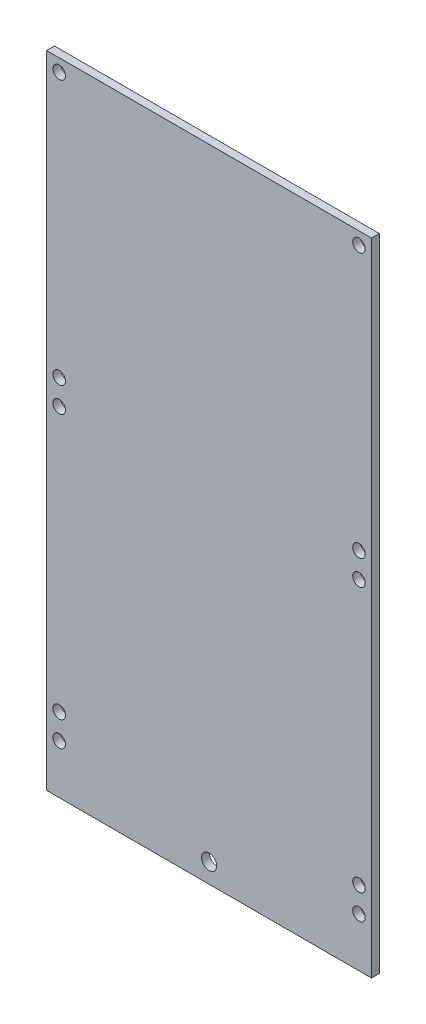
SolidWorks part; units mm, degrees
ref_plane "Front Plane" through (0, 0, 0) normal (0, 0, 1) x (1, 0, 0)
ref_plane "Top Plane" through (0, 0, 0) normal (0, 1, 0) x (1, 0, 0)
ref_plane "Right Plane" through (0, 0, 0) normal (1, 0, 0) x (0, 0, -1)
sketch "Sketch1" plane through (0, 0, 0) normal (0, 0, 1) x (1, 0, 0)
  line L1 (0, 0) -> (83, 0)
  line L2 (0, 0) -> (0, 327.5)
  line L3 (0, 327.5) -> (83, 327.5)
  line L4 (83, 0) -> (83, 327.5)
  dimension "D1" = 83
  dimension "D2" = 327.5
extrude "Boss-Extrude1" add sketch "Sketch1" along normal blind 2
sketch "Sketch2" plane through (0, 0, 2) normal (0, 0, 1) x (1, 0, 0)
  line L0 (0, 327.5) -> (0, 0) construction
  line L1 (83, 327.5) -> (0, 327.5) construction
  line L2 (0, 0) -> (83, 0) construction
  circle A0 centre (3.2, 314.9) radius 1.6
  circle A1 centre (3.2, 308.5) radius 1.6
  circle A2 centre (79.8, 314.9) radius 1.6
  circle A3 centre (79.8, 308.5) radius 1.6
  circle A4 centre (3.2, 240.925) radius 1.6
  circle A5 centre (3.2, 234.525) radius 1.6
  circle A6 centre (79.8, 240.925) radius 1.6
  circle A7 centre (79.8, 234.525) radius 1.6
  circle A8 centre (3.2, 166.95) radius 1.6
  circle A9 centre (3.2, 160.55) radius 1.6
  circle A10 centre (79.8, 166.95) radius 1.6
  circle A11 centre (79.8, 160.55) radius 1.6
  circle A12 centre (3.2, 92.975) radius 1.6
  circle A13 centre (3.2, 86.575) radius 1.6
  circle A14 centre (79.8, 92.975) radius 1.6
  circle A15 centre (79.8, 86.575) radius 1.6
  circle A16 centre (3.2, 19) radius 1.6
  circle A17 centre (3.2, 12.6) radius 1.6
  circle A18 centre (79.8, 19) radius 1.6
  circle A19 centre (79.8, 12.6) radius 1.6
  dimension "D1" = 3.2
  dimension "D4" = 3.2
  dimension "D2" = 3.2
  dimension "D3" = 12.6
  dimension "D5" = 6.4
  dimension "D6" = 3.2
  dimension "D9" = 12.6
  dimension "D7" = 2
  dimension "D8" = 5
extrude "Cut-Extrude1" cut sketch "Sketch2" against normal blind 2
sketch "Sketch3" plane through (0, 0, 2) normal (0, 0, 1) x (1, 0, 0)
  line L0 (83, 327.5) -> (0, 327.5) construction
  line L1 (0, 327.5) -> (0, 0) construction
  line L2 (83, 0) -> (83, 327.5) construction
  line L3 (0, 0) -> (83, 0) construction
  circle A0 centre (41.5, 322.524) radius 1.93
  circle A1 centre (41.5, 4.976) radius 1.93
  dimension "D1" = 3.86
  dimension "D5" = 3.86
  dimension "D2" = 4.976
  dimension "D3" = 41.5
  dimension "D4" = 41.5
  dimension "D6" = 41.5
  dimension "D7" = 41.5
  dimension "D8" = 4.976
extrude "Cut-Extrude2" cut sketch "Sketch3" against normal blind 2
sketch "Sketch4" plane through (0, 0, 2) normal (0, 0, 1) x (1, 0, 0)
  line L0 (83, 0) -> (83, 327.5) construction
  line L1 (-33.4077, 344.9309) -> (83, 344.9309)
  line L2 (-33.4077, 344.9309) -> (-33.4077, 163.75)
  line L3 (-33.4077, 163.75) -> (83, 163.75)
  line L4 (83, 344.9309) -> (83, 163.75)
  line L5 (83, 327.5) -> (0, 327.5) construction
  line L6 (0, 0) -> (83, 0) construction
  dimension "D1" = 163.75
  dimension "D2" = 163.75
extrude "Cut-Extrude3" cut sketch "Sketch4" against normal blind 10
